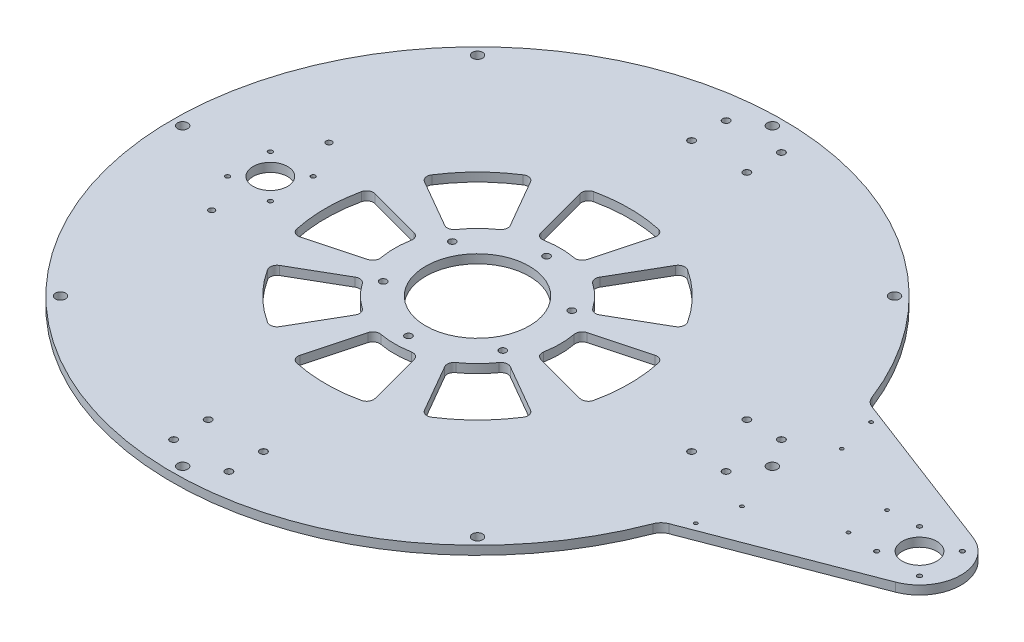
SolidWorks part; units mm, degrees
material "6061 Alloy"
ref_plane "Front Plane" through (0, 0, 0) normal (0, 0, 1) x (1, 0, 0)
ref_plane "Top Plane" through (0, 0, 0) normal (0, 1, 0) x (1, 0, 0)
ref_plane "Right Plane" through (0, 0, 0) normal (1, 0, 0) x (0, 0, -1)
sketch "Sketch1" plane through (0, 0, 0) normal (0, 1, 0) x (1, 0, 0)
  line L0 (-150, 42.4264) -> (-107.5736, 0) construction
  line L1 (-165.5, 15.5) -> (-134.5, 15.5) construction
  line L2 (-165.5, 15.5) -> (-165.5, -15.5) construction
  line L3 (-165.5, -15.5) -> (-134.5, -15.5) construction
  line L4 (-134.5, 15.5) -> (-134.5, -15.5) construction
  line L5 (-150, 42.4264) -> (-192.4264, 0) construction
  line L6 (-107.5736, 0) -> (-150, -42.4264) construction
  line L7 (-192.4264, 0) -> (-150, -42.4264) construction
  line L8 (207.8846, 75) -> (330.717, 28.0205)
  line L9 (115, 35) -> (205, 35) construction
  line L10 (115, 35) -> (115, -35) construction
  line L11 (115, -35) -> (205, -35) construction
  line L12 (205, 35) -> (205, -35) construction
  line L13 (207.8846, -75) -> (330.717, -28.0205)
  line L14 (207.8846, 75) -> (207.8846, -75) construction
  line L15 (0, 0) -> (37.5, 0) construction
  line L16 (304.5, 15.5) -> (335.5, 15.5) construction
  line L17 (304.5, 15.5) -> (304.5, -15.5) construction
  line L18 (304.5, -15.5) -> (335.5, -15.5) construction
  line L19 (335.5, 15.5) -> (335.5, -15.5) construction
  line L24 (221.5179, 63.4493) -> (227.5782, 36.113) construction
  line L25 (350, 0) -> (221, 0) construction
  line L26 (224.5481, 49.7811) -> (0, 0) construction
  line L27 (282.5, 14) -> (282.5, -14) construction
  line L28 (-20, 200) -> (-20, 175) construction
  line L33 (0, 200) -> (0, 175) construction
  line L34 (16.7734, 62.5991) -> (27.1452, 101.3072)
  line L36 (-27.1452, 101.3072) -> (-16.7734, 62.5991)
  line L52 (52.4404, 90.8295) -> (32.4037, 56.1249)
  line L53 (56.1249, 32.4037) -> (90.8295, 52.4404)
  line L54 (101.3072, 27.1452) -> (62.5991, 16.7734)
  line L55 (62.5991, -16.7734) -> (101.3072, -27.1452)
  line L56 (90.8295, -52.4404) -> (56.1249, -32.4037)
  line L57 (32.4037, -56.1249) -> (52.4404, -90.8295)
  line L58 (27.1452, -101.3072) -> (16.7734, -62.5991)
  line L59 (-16.7734, -62.5991) -> (-27.1452, -101.3072)
  line L60 (-52.4404, -90.8295) -> (-32.4037, -56.1249)
  line L61 (-56.1249, -32.4037) -> (-90.8295, -52.4404)
  line L62 (-101.3072, -27.1452) -> (-62.5991, -16.7734)
  line L63 (-62.5991, 16.7734) -> (-101.3072, 27.1452)
  line L64 (-90.8295, 52.4404) -> (-56.1249, 32.4037)
  line L65 (-32.4037, 56.1249) -> (-52.4404, 90.8295)
  line L66 (0, 175) -> (0, 0) construction
  circle A0 centre (0, 0) radius 221
  circle A1 centre (0, 0) radius 213.5 construction
  circle A2 centre (0, 213.5) radius 3 construction
  circle A3 centre (150.9673, 150.9673) radius 3 construction
  circle A4 centre (213.5, 0) radius 3 construction
  circle A5 centre (150.9673, -150.9673) radius 3 construction
  circle A6 centre (0, -213.5) radius 3 construction
  circle A7 centre (-150.9673, -150.9673) radius 3 construction
  circle A8 centre (0, 0) radius 37.5
  circle A9 centre (-150, 0) radius 12.5
  circle A10 centre (-165.5, 15.5) radius 1.5 construction
  circle A11 centre (-134.5, 15.5) radius 1.5 construction
  circle A12 centre (-134.5, -15.5) radius 1.5 construction
  circle A13 centre (-165.5, -15.5) radius 1.5 construction
  circle A14 centre (-150, 42.4264) radius 1.5 construction
  circle A15 centre (-107.5736, 0) radius 1.5 construction
  circle A16 centre (-150, -42.4264) radius 1.5 construction
  circle A17 centre (-192.4264, 0) radius 1.5 construction
  circle A18 centre (205, 35) radius 2.5 construction
  circle A19 centre (205, -35) radius 2.5 construction
  circle A20 centre (115, 35) radius 2.5 construction
  circle A21 centre (115, -35) radius 2.5 construction
  arc A22 (330.717, 28.0205) -> (330.717, -28.0205) centre (320, 0) cw
  circle A23 centre (320, 0) radius 12.5
  circle A24 centre (335.5, 15.5) radius 1.5 construction
  circle A25 centre (304.5, 15.5) radius 1.5 construction
  circle A26 centre (304.5, -15.5) radius 1.5 construction
  circle A27 centre (335.5, -15.5) radius 1.5 construction
  circle A36 centre (-213.5, 0) radius 3 construction
  circle A37 centre (-150.9673, 150.9673) radius 3 construction
  arc A38 (218.827, 70.8149) -> (218.827, -70.8149) centre (0, 0) cw construction
  circle A39 centre (221.5179, 63.4493) radius 1.5 construction
  circle A40 centre (227.5782, 36.113) radius 1.5 construction
  circle A41 centre (227.5782, -36.113) radius 1.5 construction
  circle A42 centre (221.5179, -63.4493) radius 1.5 construction
  circle A43 centre (282.5, 14) radius 1.5 construction
  circle A44 centre (282.5, -14) radius 1.5 construction
  circle A45 centre (-20, 200) radius 3 construction
  circle A46 centre (-20, 175) radius 3 construction
  circle A47 centre (20, 175) radius 3 construction
  circle A48 centre (20, 200) radius 3 construction
  circle A49 centre (200, 20) radius 3 construction
  circle A50 centre (200, -20) radius 3 construction
  circle A51 centre (175, -20) radius 3 construction
  circle A52 centre (175, 20) radius 3 construction
  circle A53 centre (20, -200) radius 3 construction
  circle A54 centre (-20, -200) radius 3 construction
  circle A55 centre (-20, -175) radius 3 construction
  circle A56 centre (20, -175) radius 3 construction
  circle A57 centre (-200, -20) radius 3 construction
  circle A58 centre (-200, 20) radius 3 construction
  circle A59 centre (-175, 20) radius 3 construction
  circle A60 centre (-175, -20) radius 3 construction
  circle A61 centre (0, 0) radius 50 construction
  circle A62 centre (0, 50) radius 3 construction
  circle A63 centre (43.3013, 25) radius 3 construction
  circle A64 centre (43.3013, -25) radius 3 construction
  circle A65 centre (0, -50) radius 3 construction
  circle A66 centre (-43.3013, -25) radius 3 construction
  circle A67 centre (-43.3013, 25) radius 3 construction
  arc A68 (-11.025, 58.9784) -> (11.025, 58.9784) centre (0, 0) cw
  arc A69 (-23.3782, 107.487) -> (23.3782, 107.487) centre (0, 0) cw
  arc A84 (-16.7734, 62.5991) -> (-11.025, 58.9784) centre (-11.9438, 63.8932) ccw
  arc A85 (16.7734, 62.5991) -> (11.025, 58.9784) centre (11.9438, 63.8932) cw
  arc A86 (27.1452, 101.3072) -> (23.3782, 107.487) centre (22.3155, 102.6013) ccw
  arc A87 (-27.1452, 101.3072) -> (-23.3782, 107.487) centre (-22.3155, 102.6013) cw
  arc A88 (52.4404, 90.8295) -> (59.4739, 92.5357) centre (56.7706, 88.3295) cw
  arc A89 (32.4037, 56.1249) -> (33.9082, 49.4999) centre (36.7338, 53.6249) ccw
  arc A90 (33.9082, 49.4999) -> (49.4999, 33.9082) centre (0, 0) cw
  arc A91 (56.1249, 32.4037) -> (49.4999, 33.9082) centre (53.6249, 36.7338) cw
  arc A92 (90.8295, 52.4404) -> (92.5357, 59.4739) centre (88.3295, 56.7706) ccw
  arc A93 (59.4739, 92.5357) -> (92.5357, 59.4739) centre (0, 0) cw
  arc A94 (101.3072, 27.1452) -> (107.487, 23.3782) centre (102.6013, 22.3155) cw
  arc A95 (62.5991, 16.7734) -> (58.9784, 11.025) centre (63.8932, 11.9438) ccw
  arc A96 (58.9784, 11.025) -> (58.9784, -11.025) centre (0, 0) cw
  arc A97 (62.5991, -16.7734) -> (58.9784, -11.025) centre (63.8932, -11.9438) cw
  arc A98 (101.3072, -27.1452) -> (107.487, -23.3782) centre (102.6013, -22.3155) ccw
  arc A99 (107.487, 23.3782) -> (107.487, -23.3782) centre (0, 0) cw
  arc A100 (90.8295, -52.4404) -> (92.5357, -59.4739) centre (88.3295, -56.7706) cw
  arc A101 (56.1249, -32.4037) -> (49.4999, -33.9082) centre (53.6249, -36.7338) ccw
  arc A102 (49.4999, -33.9082) -> (33.9082, -49.4999) centre (0, 0) cw
  arc A103 (32.4037, -56.1249) -> (33.9082, -49.4999) centre (36.7338, -53.6249) cw
  arc A104 (52.4404, -90.8295) -> (59.4739, -92.5357) centre (56.7706, -88.3295) ccw
  arc A105 (92.5357, -59.4739) -> (59.4739, -92.5357) centre (0, 0) cw
  arc A106 (27.1452, -101.3072) -> (23.3782, -107.487) centre (22.3155, -102.6013) cw
  arc A107 (16.7734, -62.5991) -> (11.025, -58.9784) centre (11.9438, -63.8932) ccw
  arc A108 (11.025, -58.9784) -> (-11.025, -58.9784) centre (0, 0) cw
  arc A109 (-16.7734, -62.5991) -> (-11.025, -58.9784) centre (-11.9438, -63.8932) cw
  arc A110 (-27.1452, -101.3072) -> (-23.3782, -107.487) centre (-22.3155, -102.6013) ccw
  arc A111 (23.3782, -107.487) -> (-23.3782, -107.487) centre (0, 0) cw
  arc A112 (-52.4404, -90.8295) -> (-59.4739, -92.5357) centre (-56.7706, -88.3295) cw
  arc A113 (-32.4037, -56.1249) -> (-33.9082, -49.4999) centre (-36.7338, -53.6249) ccw
  arc A114 (-33.9082, -49.4999) -> (-49.4999, -33.9082) centre (0, 0) cw
  arc A115 (-56.1249, -32.4037) -> (-49.4999, -33.9082) centre (-53.6249, -36.7338) cw
  arc A116 (-90.8295, -52.4404) -> (-92.5357, -59.4739) centre (-88.3295, -56.7706) ccw
  arc A117 (-59.4739, -92.5357) -> (-92.5357, -59.4739) centre (0, 0) cw
  arc A118 (-101.3072, -27.1452) -> (-107.487, -23.3782) centre (-102.6013, -22.3155) cw
  arc A119 (-62.5991, -16.7734) -> (-58.9784, -11.025) centre (-63.8932, -11.9438) ccw
  arc A120 (-58.9784, -11.025) -> (-58.9784, 11.025) centre (0, 0) cw
  arc A121 (-62.5991, 16.7734) -> (-58.9784, 11.025) centre (-63.8932, 11.9438) cw
  arc A122 (-101.3072, 27.1452) -> (-107.487, 23.3782) centre (-102.6013, 22.3155) ccw
  arc A123 (-107.487, -23.3782) -> (-107.487, 23.3782) centre (0, 0) cw
  arc A124 (-90.8295, 52.4404) -> (-92.5357, 59.4739) centre (-88.3295, 56.7706) cw
  arc A125 (-56.1249, 32.4037) -> (-49.4999, 33.9082) centre (-53.6249, 36.7338) ccw
  arc A126 (-49.4999, 33.9082) -> (-33.9082, 49.4999) centre (0, 0) cw
  arc A127 (-32.4037, 56.1249) -> (-33.9082, 49.4999) centre (-36.7338, 53.6249) cw
  arc A128 (-52.4404, 90.8295) -> (-59.4739, 92.5357) centre (-56.7706, 88.3295) ccw
  arc A129 (-92.5357, 59.4739) -> (-59.4739, 92.5357) centre (0, 0) cw
  point P18 (0, 0)
  point P24 (-150, 15.5)
  point P26 (-165.5, 0)
  point P46 (205, 0)
  point P52 (207.8846, 0)
  point P58 (320, 15.5)
  point P59 (304.5, 0)
  point P69 (0, 110)
  point P80 (0, 0)
  point P101 (224.5481, 49.7811)
  point P103 (282.5, 0)
  point P154 (0, 0)
  point P173 (0, 0)
  point P238 (0, 0)
  dimension "D2" = 442
  dimension "D3" = 427
  dimension "D4" = 6
  dimension "D5" = 75
  dimension "D6" = 25
  dimension "D9" = 3
  dimension "D11" = 3
  dimension "D12" = 5
  dimension "D18" = 25
  dimension "D19" = 30
  dimension "D21" = 3
  dimension "D24" = 100
  dimension "D26" = 230
  dimension "D28" = 3
  dimension "D29" = 12.5
  dimension "D30" = 37.5
  dimension "D33" = 6
  dimension "D22" = 40
  dimension "D23" = 175
  dimension "D25" = 6
  dimension "D32" = 60
  dimension "D35" = 110
  dimension "D38" = 5
  dimension "D7" = 150
  dimension "D8" = 31
  dimension "D10" = 60
  dimension "D13" = 70
  dimension "D14" = 90
  dimension "D15" = 205
  dimension "D16" = 320
  dimension "D17" = 150
  dimension "D20" = 31
  dimension "D27" = 28
  dimension "D34" = 25
  dimension "D36" = 30
  dimension "D1" = 8
  dimension "D37" = 4
extrude "Boss-Extrude1" add sketch "Sketch1" against normal blind 6.35 contours A0 A9 A8 | A22 L8 A0 L13
hole_wizard "M7 Clearance Hole1" positions "3DSketch1" profile "Sketch2" hole size "M7" standard "ANSI Metric" end condition through all
sketch3d "3DSketch1"
  point P0 (0, 0, -213.5)
  point P2 (150.9673, 0, -150.9673)
  point P4 (213.5, 0, 0)
  point P6 (150.9673, 0, 150.9673)
  point P8 (0, 0, 213.5)
  point P10 (-150.9673, 0, 150.9673)
  point P25 (-150.9673, 0, -150.9673)
  point P27 (-213.5, 0, 0)
sketch "Sketch2" plane through (0, 0, -213.5) normal (1, 0, 0) x (0, 0, 1)
  line L0 (0, 0) -> (0, 6.35)
  line L1 (0, 6.35) -> (3.7, 6.35)
  line L2 (3.7, 6.35) -> (3.7, 0)
  line L5 (3.7, 0) -> (0, 0)
  line L11 (0, -6.35) -> (0, 107.95) construction
  dimension "Thru Hole Dia." = 7.4
  dimension "Thru Hole Depth" = 6.35
hole_wizard "M3 Clearance Hole3" positions "3DSketch2" profile "Sketch3" hole size "M3" standard "ANSI Metric" end condition through all
sketch3d "3DSketch2"
  point P0 (-165.5, 0, -15.5)
  point P2 (-134.5, 0, -15.5)
  point P4 (-134.5, 0, 15.5)
  point P6 (-165.5, 0, 15.5)
sketch "Sketch3" plane through (-165.5, 0, -15.5) normal (1, 0, 0) x (0, 0, 1)
  line L0 (0, 0) -> (0, 6.35)
  line L1 (0, 6.35) -> (1.6, 6.35)
  line L2 (1.6, 6.35) -> (1.6, 0)
  line L5 (1.6, 0) -> (0, 0)
  line L11 (0, -6.35) -> (0, 107.95) construction
  dimension "Thru Hole Dia." = 3.2
  dimension "Thru Hole Depth" = 6.35
hole_wizard "Tap Drill for M5x0.8 Tap2" positions "3DSketch3" profile "Sketch4" hole size "M5x0.8" standard "ANSI Metric" end condition through all
sketch3d "3DSketch3"
  point P2 (-150, 0, 42.4264)
  point P6 (-150, 0, -42.4264)
  point P18 (0, 0, 0)
  point P19 (0, 0, 0)
sketch "Sketch4" plane through (-150, 0, 42.4264) normal (1, 0, 0) x (0, 0, 1)
  line L0 (0, 0) -> (0, 6.35)
  line L1 (0, 6.35) -> (2.1, 6.35)
  line L2 (2.1, 6.35) -> (2.1, 0)
  line L5 (2.1, 0) -> (0, 0)
  line L11 (0, -6.35) -> (0, 107.95) construction
  dimension "Thru Hole Dia." = 4.2
  dimension "Thru Hole Depth" = 6.35
hole_wizard "Tap Drill for M5x0.8 Tap1" positions "3DSketch4" profile "Sketch5" hole size "M5x0.8" standard "ANSI Metric"
sketch3d "3DSketch4"
  line L0 (115, 0, -35) -> (115, 0, 35) construction
  line L1 (115, 0, -35) -> (205, 0, -35) construction
  point P0 (115, 0, 35)
  point P2 (115, 0, -35)
  point P4 (205, 0, -35)
  point P6 (205, 0, 35)
sketch "Sketch5" plane through (115, 0, 35) normal (1, 0, 0) x (0, 0, 1)
  line L0 (0, 0) -> (0, 6.35)
  line L1 (0, 6.35) -> (2.1, 6.35)
  line L2 (2.1, 6.35) -> (2.1, 0)
  line L5 (2.1, 0) -> (0, 0)
  line L11 (0, -6.35) -> (0, 107.95) construction
  dimension "Thru Hole Dia." = 4.2
  dimension "Thru Hole Depth" = 6.35
fillet "Fillet1" radius 10 2 edges at (207.8846, -3.175, -75) (207.8846, -3.175, 75)
hole_wizard "M3 Clearance Hole2" positions "3DSketch5" profile "Sketch6" hole size "M3" standard "ANSI Metric" end condition through all
sketch3d "3DSketch5"
  point P0 (304.5, 0, 15.5)
  point P2 (304.5, 0, -15.5)
  point P4 (335.5, 0, -15.5)
  point P6 (335.5, 0, 15.5)
sketch "Sketch6" plane through (304.5, 0, 15.5) normal (1, 0, 0) x (0, 0, 1)
  line L0 (0, 0) -> (0, 6.35)
  line L1 (0, 6.35) -> (1.6, 6.35)
  line L2 (1.6, 6.35) -> (1.6, 0)
  line L5 (1.6, 0) -> (0, 0)
  line L11 (0, -6.35) -> (0, 107.95) construction
  dimension "Thru Hole Dia." = 3.2
  dimension "Thru Hole Depth" = 6.35
hole_wizard "Tap Drill for M6x1.0 Tap1" positions "3DSketch6" profile "Sketch7" hole size "M6x1.0" standard "ANSI Metric" end condition through all
sketch3d "3DSketch6"
  point P48 (-20, 0, 175)
  point P50 (20, 0, 175)
  point P52 (-20, 0, 200)
  point P54 (20, 0, 200)
  point P61 (200, 0, 20)
  point P63 (175, 0, -20)
  point P65 (200, 0, -20)
  point P69 (175, 0, 20)
  point P72 (-20, 0, -200)
  point P74 (20, 0, -200)
  point P76 (20, 0, -175)
  point P78 (-20, 0, -175)
sketch "Sketch7" plane through (-20, 0, 175) normal (1, 0, 0) x (0, 0, 1)
  line L0 (0, 0) -> (0, 6.35)
  line L1 (0, 6.35) -> (2.5, 6.35)
  line L2 (2.5, 6.35) -> (2.5, 0.025)
  line L3 (2.5, 0.025) -> (2.525, 0)
  line L5 (2.525, 0) -> (0, 0)
  line L6 (-2.5, 0.025) -> (-2.525, 0) construction
  line L11 (0, -6.35) -> (0, 107.95) construction
  dimension "Thru Hole Dia." = 5
  dimension "Thru Hole Depth" = 6.35
  dimension "Near C'Sink Dia." = 5.05
  dimension "Near C'Sink Angle" = 90
hole_wizard "Tap Drill for M3x0.5 Tap2" positions "3DSketch7" profile "Sketch8" hole size "M3x0.5" standard "ANSI Metric" end condition through all
sketch3d "3DSketch7"
  point P0 (221.5179, 0, -63.4493)
  point P2 (227.5782, 0, -36.113)
  point P4 (227.5782, 0, 36.113)
  point P6 (221.5179, 0, 63.4493)
  point P17 (282.5, 0, -14)
  point P19 (282.5, 0, 14)
sketch "Sketch8" plane through (221.5179, 0, -63.4493) normal (1, 0, 0) x (0, 0, 1)
  line L0 (0, 0) -> (0, 6.35)
  line L1 (0, 6.35) -> (1.25, 6.35)
  line L2 (1.25, 6.35) -> (1.25, 0)
  line L5 (1.25, 0) -> (0, 0)
  line L11 (0, -6.35) -> (0, 107.95) construction
  dimension "Thru Hole Dia." = 2.5
  dimension "Thru Hole Depth" = 6.35
hole_wizard "Tap Drill for M6x1.0 Tap2" positions "3DSketch8" profile "Sketch9" hole size "M6x1.0" standard "ANSI Metric" end condition up to next
sketch3d "3DSketch8"
  point P0 (0, 0, -50)
  point P2 (43.3013, 0, -25)
  point P4 (-43.3013, 0, -25)
  point P6 (-43.3013, 0, 25)
  point P8 (0, 0, 50)
  point P10 (43.3013, 0, 25)
sketch "Sketch9" plane through (0, 0, -50) normal (1, 0, 0) x (0, 0, 1)
  line L0 (0, 0) -> (0, 6.35)
  line L1 (0, 6.35) -> (2.5, 6.35)
  line L2 (2.5, 6.35) -> (2.5, 0)
  line L5 (2.5, 0) -> (0, 0)
  line L11 (0, -6.35) -> (0, 107.95) construction
  dimension "Thru Hole Dia." = 5
  dimension "Thru Hole Depth" = 6.35
